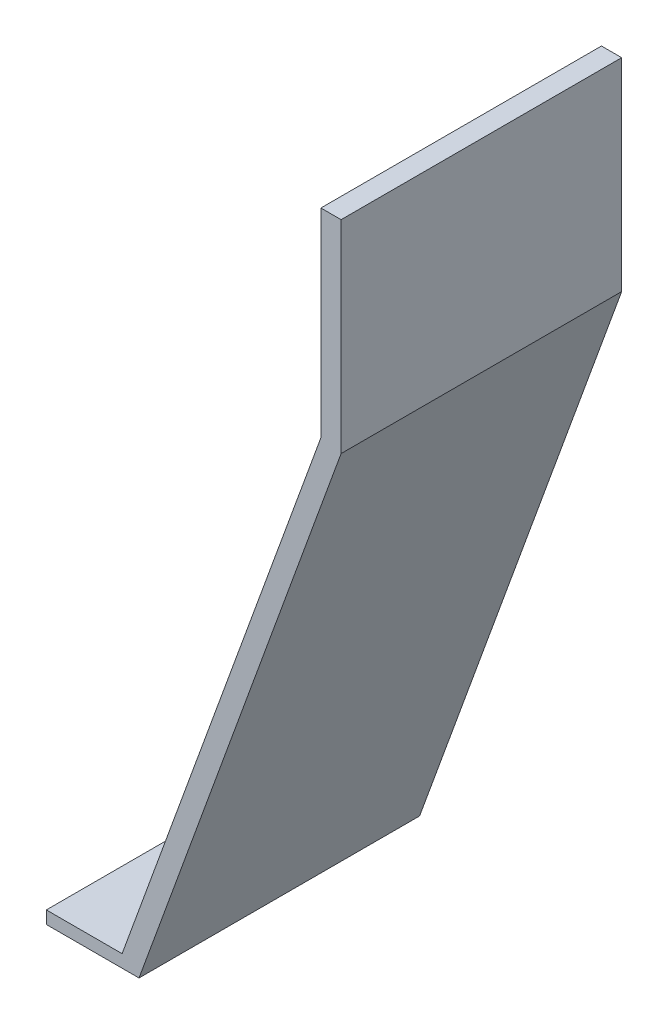
SolidWorks part; units mm, degrees
ref_plane "Front Plane" through (0, 0, 0) normal (0, 0, 1) x (1, 0, 0)
ref_plane "Top Plane" through (0, 0, 0) normal (0, 1, 0) x (1, 0, 0)
ref_plane "Right Plane" through (0, 0, 0) normal (1, 0, 0) x (0, 0, -1)
sketch "Croquis1" plane through (0, 0, 0) normal (0, 0, 1) x (1, 0, 0)
  line L0 (0, 0) -> (18.3468, 0)
  line L1 (18.3468, 0) -> (58.3468, 109.8991)
  line L2 (58.3468, 109.8991) -> (58.3468, 150)
  line L3 (58.3468, 150) -> (54.3468, 150)
  line L4 (54.3468, 150) -> (54.3468, 110.6044)
  line L5 (54.3468, 110.6044) -> (15, 2.5)
  line L6 (15, 2.5) -> (0, 2.5)
  line L7 (0, 2.5) -> (0, 0)
  point P4 (0, 0)
  point P10 (18.0567, 0)
  point P11 (0, 0)
  point P12 (45.1511, 37.8521)
  point P13 (58.3468, 129.9495)
  point P14 (0, 0)
  dimension "D1" = 2.5
  dimension "D2" = 15
  dimension "D3" = 4
  dimension "D4" = 150
  dimension "D5" = 40
  dimension "D6" = 4
  dimension "D7" = 110
extrude "Saliente-Extruir1" add sketch "Croquis1" along normal blind 55.54
